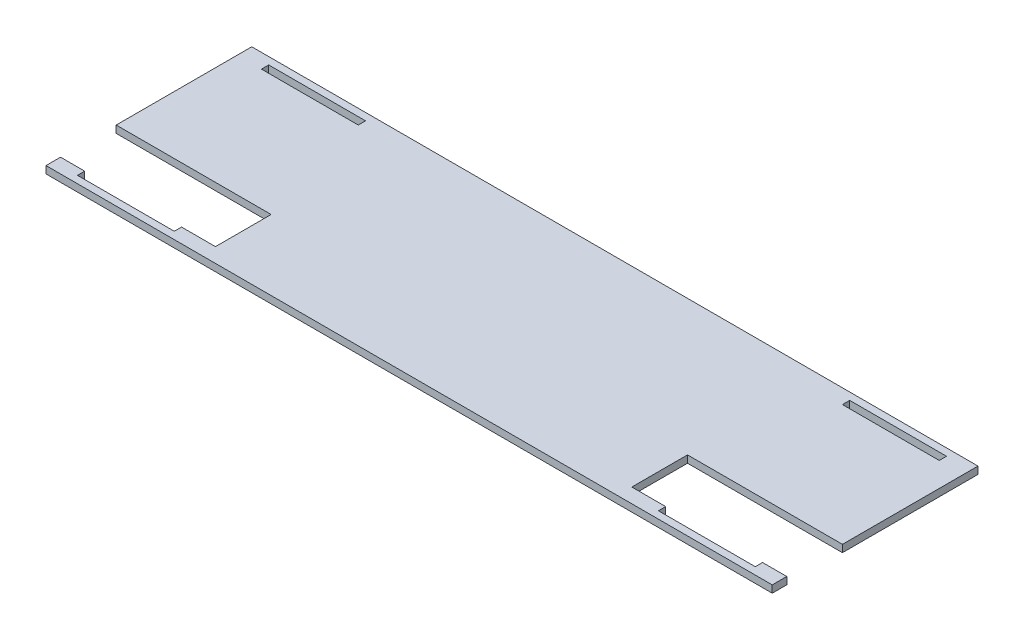
SolidWorks part; units mm, degrees
ref_plane "Front Plane" through (0, 0, 0) normal (0, 0, 1) x (1, 0, 0)
ref_plane "Top Plane" through (0, 0, 0) normal (0, 1, 0) x (1, 0, 0)
ref_plane "Right Plane" through (0, 0, 0) normal (1, 0, 0) x (0, 0, -1)
sketch "Sketch1" plane through (0, 0, 0) normal (0, 1, 0) x (1, 0, 0)
  line L1 (0, 0) -> (-300, 0)
  line L2 (0, 0) -> (0, 85)
  line L3 (0, 85) -> (-300, 85)
  line L4 (-300, 0) -> (-300, 85)
  dimension "D1" = 300
  dimension "D2" = 85
extrude "Boss-Extrude1" add sketch "Sketch1" along normal blind 3
sketch "Sketch2" plane through (0, 3, 0) normal (0, 1, 0) x (1, 0, 0)
  line L0 (-300, 85) -> (-300, 0) construction
  line L1 (-290, 3) -> (-250, 3)
  line L2 (-290, 3) -> (-290, 6)
  line L3 (-290, 6) -> (-250, 6)
  line L4 (-250, 3) -> (-250, 6)
  line L5 (-300, 0) -> (0, 0) construction
  dimension "D1" = 3
  dimension "D2" = 40
  dimension "D3" = 10
  dimension "D4" = 3
extrude "Cut-Extrude1" cut sketch "Sketch2" against normal blind 3
sketch "Sketch3" plane through (0, 3, 0) normal (0, 1, 0) x (1, 0, 0)
  line L0 (0, 0) -> (0, 85) construction
  line L1 (-50, 6) -> (-10, 6)
  line L2 (-50, 6) -> (-50, 3)
  line L3 (-50, 3) -> (-10, 3)
  line L4 (-10, 6) -> (-10, 3)
  line L5 (-300, 0) -> (0, 0) construction
  dimension "D1" = 40
  dimension "D2" = 3
  dimension "D3" = 10
  dimension "D4" = 3
extrude "Cut-Extrude2" cut sketch "Sketch3" against normal blind 3
sketch "Sketch4" plane through (0, 3, 0) normal (0, 1, 0) x (1, 0, 0)
  line L0 (0, 0) -> (0, 85) construction
  line L1 (-50, 82) -> (-10, 82)
  line L2 (-50, 82) -> (-50, 79)
  line L3 (-50, 79) -> (-10, 79)
  line L4 (-10, 82) -> (-10, 79)
  line L5 (0, 85) -> (-300, 85) construction
  dimension "D1" = 40
  dimension "D2" = 3
  dimension "D3" = 10
  dimension "D4" = 3
extrude "Cut-Extrude3" cut sketch "Sketch4" against normal blind 3
sketch "Sketch5" plane through (0, 3, 0) normal (0, 1, 0) x (1, 0, 0)
  line L0 (0, 85) -> (-300, 85) construction
  line L1 (-290, 82) -> (-250, 82)
  line L2 (-290, 82) -> (-290, 79)
  line L3 (-290, 79) -> (-250, 79)
  line L4 (-250, 82) -> (-250, 79)
  dimension "D1" = 10
  dimension "D2" = 3
  dimension "D3" = 40
  dimension "D4" = 3
extrude "Cut-Extrude4" cut sketch "Sketch5" against normal blind 3
sketch "Sketch6" plane through (0, 3, 0) normal (0, 1, 0) x (1, 0, 0)
  line L0 (-300, 0) -> (0, 0) construction
  line L1 (-300, 29) -> (-236, 29)
  line L2 (-300, 29) -> (-300, 6)
  line L3 (-300, 6) -> (-236, 6)
  line L4 (-236, 29) -> (-236, 6)
  line L5 (-300, 85) -> (-300, 0) construction
  dimension "D1" = 64
  dimension "D2" = 6
  dimension "D3" = 23
  dimension "D4" = 0
extrude "Cut-Extrude6" cut sketch "Sketch6" against normal blind 3
sketch "Sketch7" plane through (0, 3, 0) normal (0, 1, 0) x (1, 0, 0)
  line L0 (0, 0) -> (0, 85) construction
  line L1 (-64, 6) -> (0, 6)
  line L2 (-64, 6) -> (-64, 29)
  line L3 (-64, 29) -> (0, 29)
  line L4 (0, 6) -> (0, 29)
  line L5 (-300, 0) -> (0, 0) construction
  dimension "D1" = 64
  dimension "D2" = 0
  dimension "D3" = 6
  dimension "D4" = 23
extrude "Cut-Extrude7" cut sketch "Sketch7" against normal blind 3
